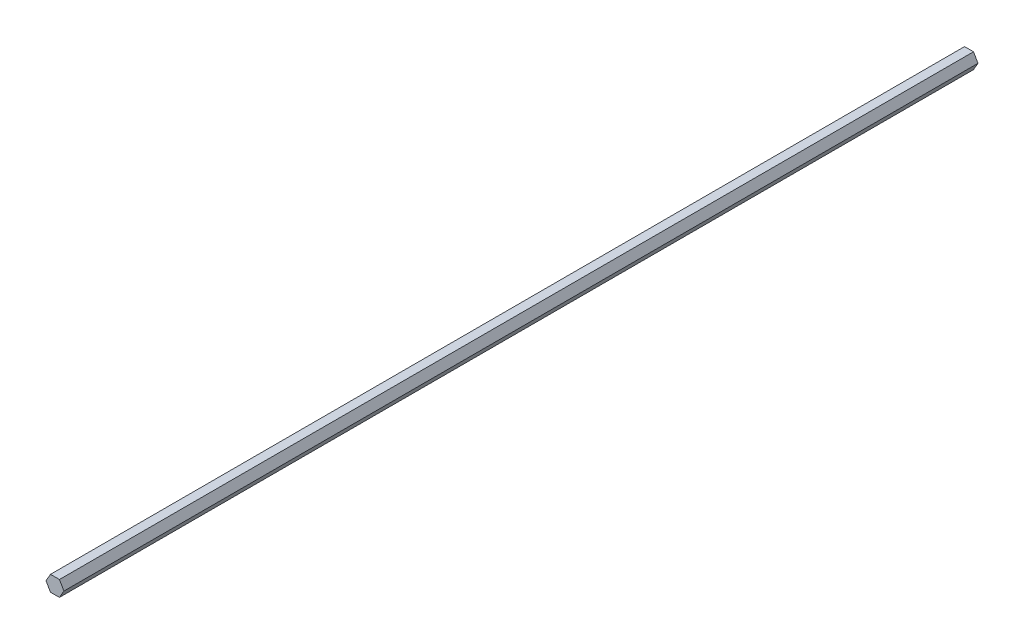
SolidWorks part; units mm, degrees
ref_plane "Front" through (0, 0, 0) normal (0, 0, 1) x (1, 0, 0)
ref_plane "Top" through (0, 0, 0) normal (0, 1, 0) x (1, 0, 0)
ref_plane "Right" through (0, 0, 0) normal (1, 0, 0) x (0, 0, -1)
sketch "草图1" plane through (0, 0, 0) normal (0, 0, 1) x (1, 0, 0)
  line L1 (-18.685, 22.3856) -> (-22.3627, 28.7556)
  line L2 (-22.3627, 28.7556) -> (-29.7181, 28.7556)
  line L3 (-29.7181, 28.7556) -> (-33.3959, 22.3856)
  line L4 (-33.3959, 22.3856) -> (-29.7181, 16.0156)
  line L5 (-29.7181, 16.0156) -> (-22.3627, 16.0156)
  line L6 (-22.3627, 16.0156) -> (-18.685, 22.3856)
  circle A0 centre (-26.0404, 22.3856) radius 6.37 construction
extrude "凸台-拉伸1" add sketch "草图1" along normal blind 750 contours L2 L3 L4 L5 L6 L1
